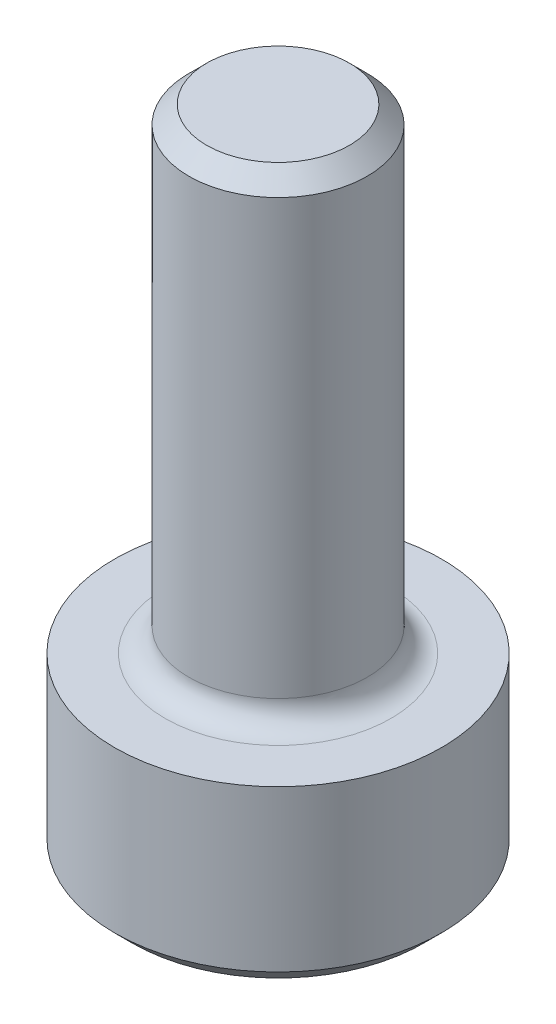
SolidWorks part; units mm, degrees
ref_plane "Front Plane" through (0, 0, 0) normal (0, 0, 1) x (1, 0, 0)
ref_plane "Top Plane" through (0, 0, 0) normal (0, 1, 0) x (1, 0, 0)
ref_plane "Right Plane" through (0, 0, 0) normal (1, 0, 0) x (0, 0, -1)
sketch "Sketch2" plane through (0, 0, 0) normal (0, 1, 0) x (1, 0, 0)
  circle A0 centre (0, 0) radius 1.5
extrude "Boss-Extrude1" add sketch "Sketch2" along normal blind 8
sketch "Sketch3" plane through (0, 0, 0) normal (0, 1, 0) x (1, 0, 0)
  circle A0 centre (0, 0) radius 2.75
  dimension "D1" = 5.5
extrude "Boss-Extrude2" add sketch "Sketch3" against normal blind 3
fillet "Fillet1" radius 0.4 1 edges at (0, 0, 1.5)
chamfer "Chamfer1" distance 0.3 angle 45 2 edges at (0, 8, 1.5) (0, -3, 2.75)
sketch "Sketch4" plane through (0, -3, 0) normal (0, -1, 0) x (1, 0, 0)
  line L1 (0, 1.4434) -> (-1.25, 0.7217)
  line L2 (-1.25, 0.7217) -> (-1.25, -0.7217)
  line L3 (-1.25, -0.7217) -> (0, -1.4434)
  line L4 (0, -1.4434) -> (1.25, -0.7217)
  line L5 (1.25, -0.7217) -> (1.25, 0.7217)
  line L6 (1.25, 0.7217) -> (0, 1.4434)
  circle A0 centre (0, 0) radius 1.25 construction
  dimension "D1" = 2.5
extrude "Cut-Extrude1" cut sketch "Sketch4" against normal blind 2.5
